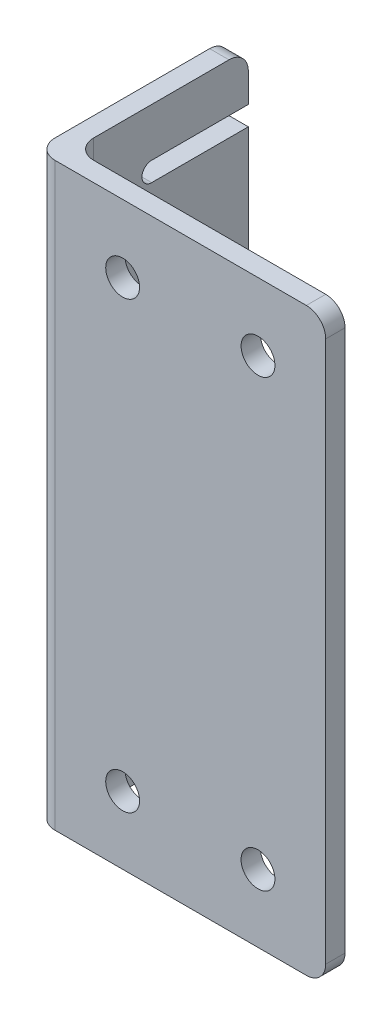
SolidWorks part; units mm, degrees
ref_plane "Plan de face" through (0, 0, 0) normal (0, 0, 1) x (1, 0, 0)
ref_plane "Plan de dessus" through (0, 0, 0) normal (0, 1, 0) x (1, 0, 0)
ref_plane "Plan de droite" through (0, 0, 0) normal (1, 0, 0) x (0, 0, -1)
sketch "Esquisse1" plane through (0, 0, 0) normal (0, 1, 0) x (1, 0, 0)
  line L0 (30, 0) -> (0, 0)
  line L1 (0, 0) -> (0, 20)
  line L2 (0, 20) -> (2, 20)
  line L3 (2, 20) -> (2, 2)
  line L4 (2, 2) -> (30, 2)
  line L5 (30, 2) -> (30, 0)
  dimension "D1" = 2
  dimension "D2" = 2
  dimension "D3" = 20
  dimension "D4" = 30
extrude "Boss.-Extru.1" add sketch "Esquisse1" along normal blind 60
sketch "Esquisse2" plane through (0, 0, 0) normal (-1, 0, 0) x (0, 0, 1)
  line L0 (-20, 60) -> (-20, 0) construction
  line L1 (-20, 55) -> (-10, 55)
  line L2 (-20, 55) -> (-20, 53)
  line L3 (-20, 53) -> (-10, 53)
  line L5 (-20, 60) -> (0, 60) construction
  line L6 (-20, 5) -> (-10, 5)
  line L7 (-20, 5) -> (-20, 7)
  line L8 (-20, 7) -> (-10, 7)
  line L10 (-20, 0) -> (0, 0) construction
  arc A0 (-10, 53) -> (-10, 55) centre (-10, 54) ccw
  arc A1 (-10, 5) -> (-10, 7) centre (-10, 6) ccw
  dimension "D1" = 10
  dimension "D2" = 2
  dimension "D3" = 5
  dimension "D4" = 2
  dimension "D5" = 5
extrude "Enlèv. mat.-Extru.1" cut sketch "Esquisse2" against normal through all
sketch "Esquisse3" plane through (0, 0, -2) normal (0, 0, -1) x (-1, 0, 0)
  line L0 (-30, 60) -> (-30, 0) construction
  line L1 (-30, 60) -> (-2, 60) construction
  line L2 (-30, 0) -> (-2, 0) construction
  line L3 (-2, 5) -> (-2, 0) construction
  circle A0 centre (-23, 53) radius 1.75
  circle A1 centre (-9, 53) radius 1.75
  circle A2 centre (-9, 7) radius 1.75
  circle A3 centre (-23, 7) radius 1.75
  point P6 (0, 0)
  point P7 (0, 0)
  point P8 (0, 0)
  point P15 (0, 0)
  point P16 (0, 0)
  point P17 (-8.3357, 53)
  point P18 (-8.1132, 10.3005)
  point P21 (-8.5314, 7)
  dimension "D1" = 3.5
  dimension "D3" = 7
  dimension "D2" = 7
  dimension "D6" = 7
  dimension "D7" = 7
  dimension "D4" = 2
  dimension "D5" = 2
extrude "Enlèv. mat.-Extru.2" cut sketch "Esquisse3" against normal through all
fillet "Congé1" radius 2 6 edges at (2, 30, -2) (0, 30, 0) (30, 0, -1) (30, 60, -1) (1, 0, -20) (1, 60, -20)
